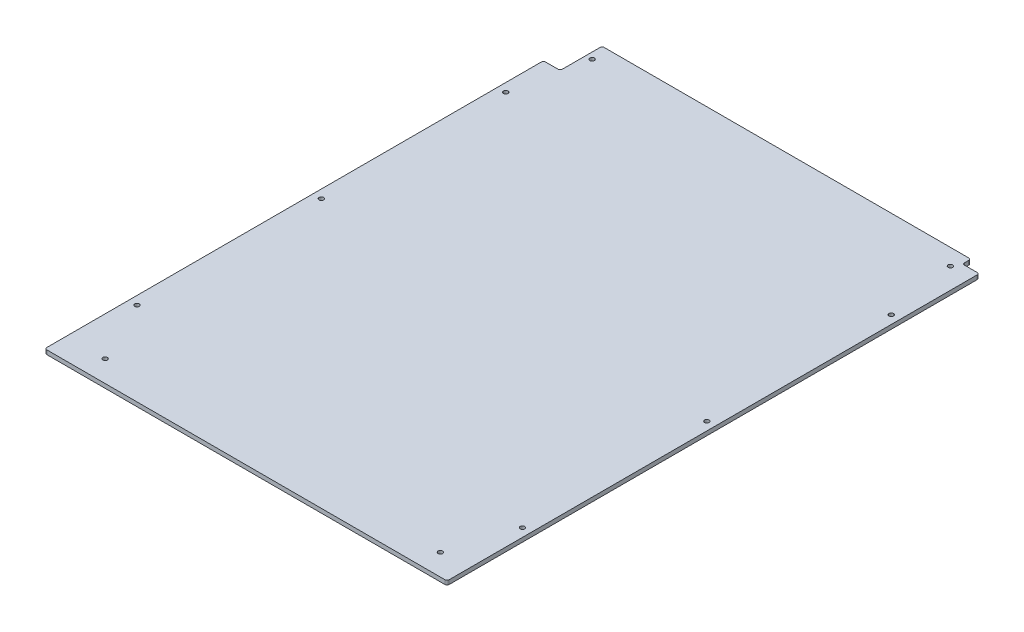
SolidWorks part; units mm, degrees
material "PE High Density"
ref_plane "Front Plane" through (0, 0, 0) normal (0, 0, 1) x (1, 0, 0)
ref_plane "Top Plane" through (0, 0, 0) normal (0, 1, 0) x (1, 0, 0)
ref_plane "Right Plane" through (0, 0, 0) normal (1, 0, 0) x (0, 0, -1)
sketch "Sketch1" plane through (0, 0, 0) normal (0, 1, 0) x (1, 0, 0)
  line L0 (0, 0) -> (0, 755.65)
  line L1 (0, 755.65) -> (25.4, 755.65)
  line L2 (25.4, 755.65) -> (25.4, 819.15)
  line L3 (25.4, 819.15) -> (584.2, 819.15)
  line L4 (584.2, 819.15) -> (584.2, 806.45)
  line L5 (584.2, 806.45) -> (609.6, 806.45)
  line L6 (609.6, 806.45) -> (609.6, 0)
  line L7 (609.6, 0) -> (0, 0)
  line L8 (596.9, 685.8) -> (596.9, 406.4) construction
  circle A1 centre (12.7, 685.8) radius 3.429
  circle A14 centre (12.7, 127) radius 3.429
  circle A16 centre (577.85, 794.512) radius 3.429
  circle A24 centre (566.928, 32.512) radius 3.429
  circle A25 centre (596.9, 127) radius 3.429 [skipped]
  circle A26 centre (596.9, 685.8) radius 3.429
  circle A27 centre (596.9, 406.4) radius 3.429
  circle A29 centre (34.925, 794.512) radius 3.429
  circle A31 centre (58.928, 32.512) radius 3.429
  circle A32 centre (596.9, 685.8) radius 3.429 [skipped]
  circle A33 centre (596.9, 499.5333) radius 3.429 [skipped]
  circle A34 centre (596.9, 313.2667) radius 3.429 [skipped]
  circle A35 centre (596.9, 127) radius 3.429
  circle A36 centre (12.7, 313.2667) radius 3.429 [skipped]
  circle A37 centre (12.7, 499.5333) radius 3.429 [skipped]
  circle A38 centre (12.7, 406.4) radius 3.429
  circle A39 centre (312.928, 32.512) radius 3.429 [skipped]
  dimension "D8" = 133.35
  dimension "D9" = 6.858
  dimension "D11" = 6.858
  dimension "D22" = 6.858
  dimension "D23" = 279.4
  dimension "D17" = 6.858
  dimension "D18" = 24.638
  dimension "D25" = 6.858
  dimension "D24" = 6.858
  dimension "D1" = 609.6
  dimension "D2" = 755.65
  dimension "D3" = 63.5
  dimension "D4" = 12.7
  dimension "D5" = 806.45
  dimension "D6" = 25.4
  dimension "D7" = 25.4
  dimension "D10" = 12.7
  dimension "D12" = 24.638
  dimension "D15" = 6.35
  dimension "D19" = 12.7
  dimension "D20" = 3
  dimension "D21" = 279.4
  dimension "D26" = 42.672
  dimension "D16" = 120.65
  dimension "D29" = 279.4
  dimension "D13" = 2
  dimension "D14" = 4
  dimension "D27" = 3
extrude "Boss-Extrude1" add sketch "Sketch1" along normal blind 6.35
fillet "Fillet1" radius 3.175 8 edges at (25.4, 3.175, -755.65) (25.4, 3.175, -819.15) (0, 3.175, -755.65) (584.2, 3.175, -806.45) (584.2, 3.175, -819.15) (609.6, 3.175, -806.45) (609.6, 3.175, 0) (0, 3.175, 0)
